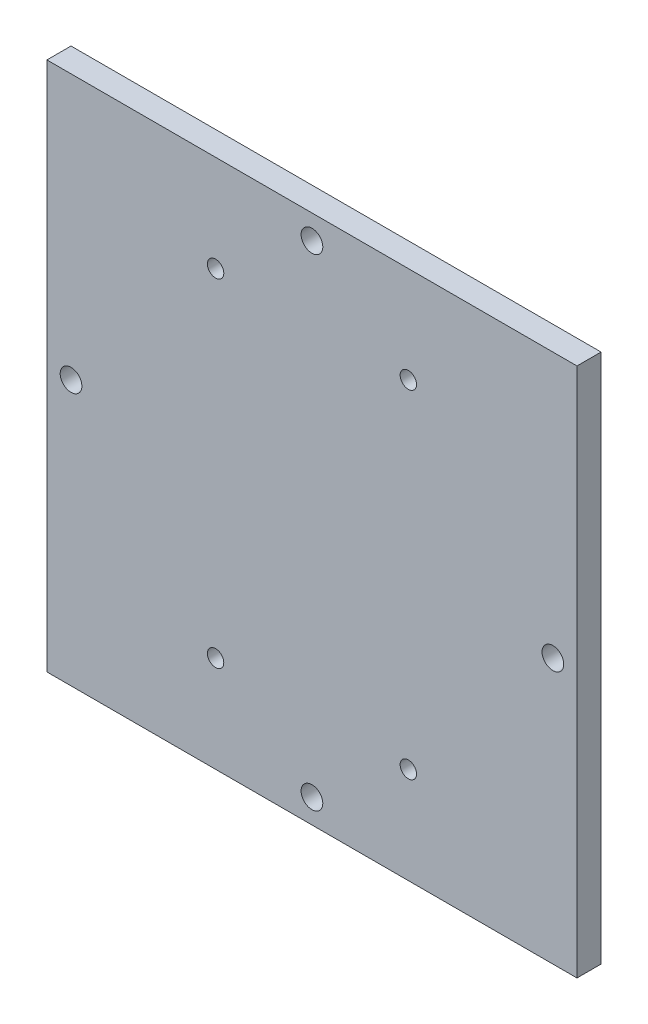
SolidWorks part; units mm, degrees
ref_plane "Ebene vorne" through (0, 0, 0) normal (0, 0, 1) x (1, 0, 0)
ref_plane "Ebene oben" through (0, 0, 0) normal (0, 1, 0) x (1, 0, 0)
ref_plane "Ebene rechts" through (0, 0, 0) normal (1, 0, 0) x (0, 0, -1)
sketch "Skizze1" plane through (0, 0, 0) normal (0, 0, 1) x (1, 0, 0)
  line L1 (-110, -110) -> (110, -110)
  line L2 (-110, -110) -> (-110, 110)
  line L3 (-110, 110) -> (110, 110)
  line L4 (110, -110) -> (110, 110)
  line L5 (-110, -110) -> (110, 110) construction
  line L6 (-110, 110) -> (110, -110) construction
  point P0 (0, 0)
  dimension "D1" = 220
extrude "Aufsatz-Linear austragen1" add sketch "Skizze1" along normal blind 10
sketch "Skizze3" plane through (0, 0, 10) normal (0, 0, 1) x (1, 0, 0)
  line L0 (0, 0) -> (162.367, 0) construction
  line L1 (0, 0) -> (0, 108.6166) construction
  line L2 (110, -110) -> (110, 110) construction
  line L3 (0, 0) -> (0, -162.367) construction
  line L4 (0, 0) -> (-162.367, 0) construction
  line L5 (0, 0) -> (0, 162.367) construction
  circle A0 centre (100, 0) radius 4.5
  circle A1 centre (0, -100) radius 4.5
  circle A2 centre (-100, 0) radius 4.5
  circle A3 centre (0, 100) radius 4.5
  point P20 (0, 0)
  dimension "D2" = 9
  dimension "D1" = 10
  dimension "D3" = 4
extrude "Schnitt-Linear austragen1" cut sketch "Skizze3" against normal through all
sketch "Skizze4" plane through (0, 0, 10) normal (0, 0, 1) x (1, 0, 0)
  line L0 (0, 0) -> (129.7076, 0) construction
  line L1 (0, 0) -> (0, 119.6829) construction
  circle A0 centre (40, 70) radius 3.4
  circle A1 centre (-40, 70) radius 3.4
  circle A2 centre (40, -70) radius 3.4
  circle A3 centre (-40, -70) radius 3.4
  dimension "D1" = 6.8
  dimension "D2" = 140
  dimension "D3" = 80
extrude "Schnitt-Linear austragen2" cut sketch "Skizze4" against normal through all
